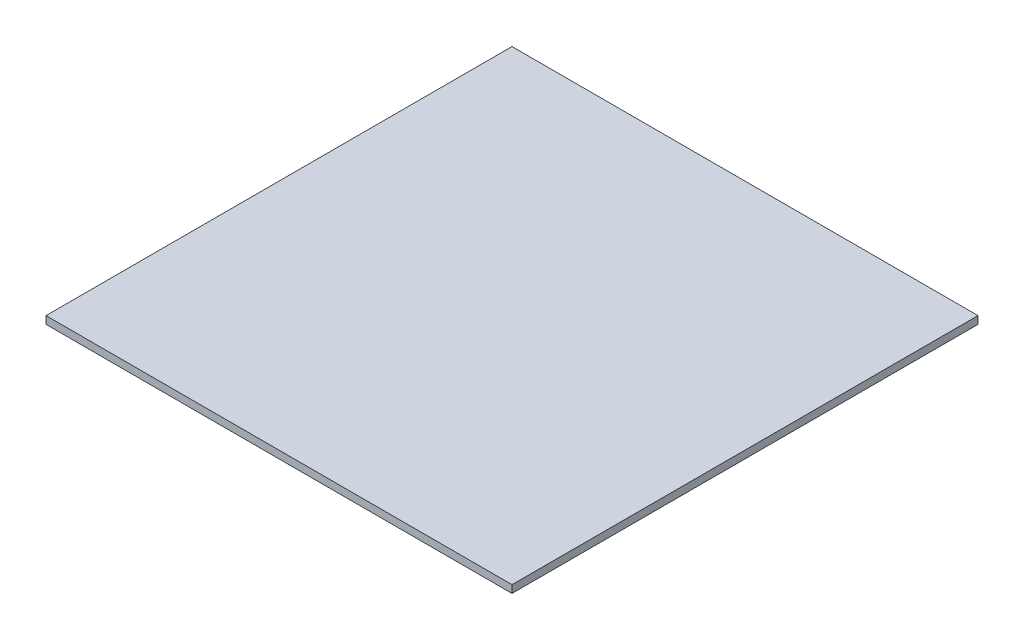
SolidWorks part; units mm, degrees
ref_plane "Front Plane" through (0, 0, 0) normal (0, 0, 1) x (1, 0, 0)
ref_plane "Top Plane" through (0, 0, 0) normal (0, 1, 0) x (1, 0, 0)
ref_plane "Right Plane" through (0, 0, 0) normal (1, 0, 0) x (0, 0, -1)
sketch "Sketch2" plane through (0, 0, 0) normal (0, 1, 0) x (1, 0, 0)
  line L1 (122.5, 122.5) -> (-122.5, 122.5)
  line L2 (122.5, 122.5) -> (122.5, -122.5)
  line L3 (122.5, -122.5) -> (-122.5, -122.5)
  line L4 (-122.5, 122.5) -> (-122.5, -122.5)
  line L5 (122.5, 122.5) -> (-122.5, -122.5) construction
  line L6 (122.5, -122.5) -> (-122.5, 122.5) construction
  point P0 (0, 0)
  dimension "D1" = 245
  dimension "D2" = 245
extrude "Boss-Extrude1" add sketch "Sketch2" along normal blind 4
